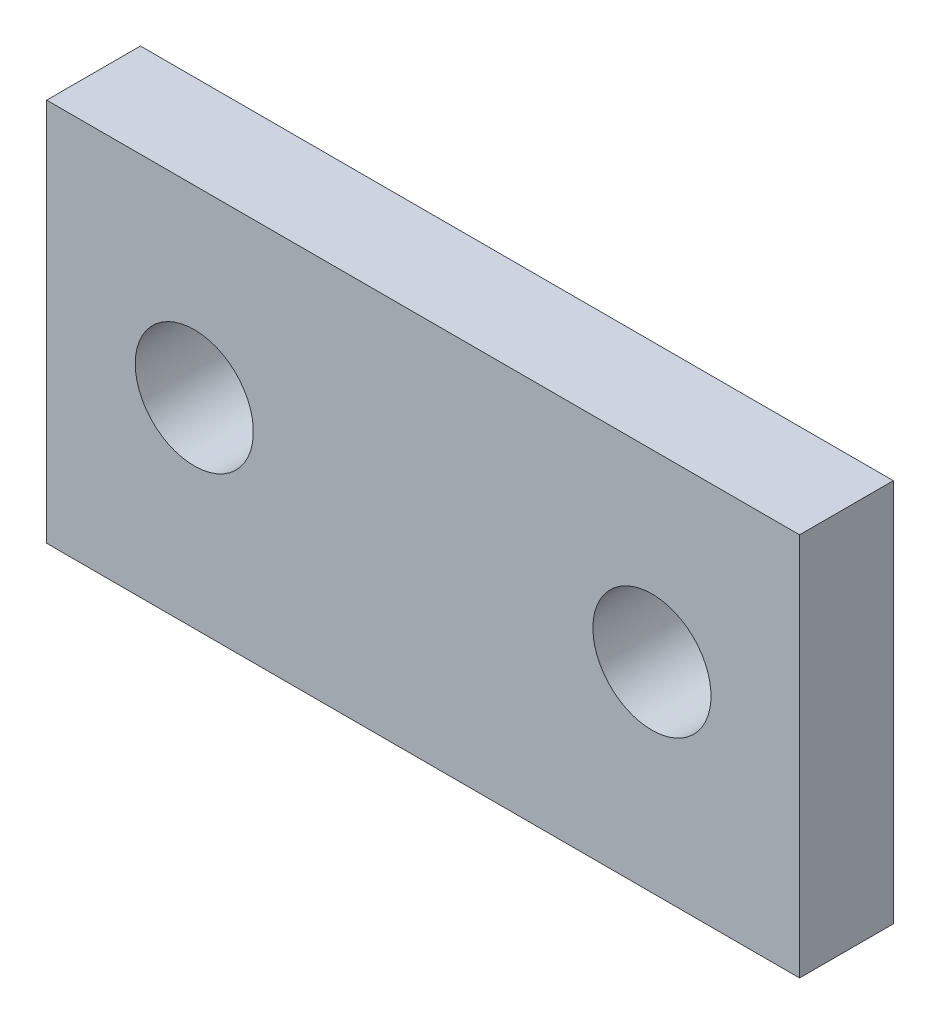
SolidWorks part; units mm, degrees
ref_plane "Front" through (0, 0, 0) normal (0, 0, 1) x (1, 0, 0)
ref_plane "Top" through (0, 0, 0) normal (0, 1, 0) x (1, 0, 0)
ref_plane "Right" through (0, 0, 0) normal (1, 0, 0) x (0, 0, -1)
sketch "Sketch1" plane through (0, 0, 0) normal (0, 0, 1) x (1, 0, 0)
  line L1 (-12.7408, 6.2308) -> (12.7592, 6.2308)
  line L2 (-12.7408, 6.2308) -> (-12.7408, -6.7692)
  line L3 (-12.7408, -6.7692) -> (12.7592, -6.7692)
  line L4 (12.7592, 6.2308) -> (12.7592, -6.7692)
  dimension "D1" = 13
  dimension "D2" = 25.5
extrude "Boss-Extrude1" add sketch "Sketch1" along normal blind 3.175
sketch "Sketch2" plane through (0, 0, 0) normal (0, 0, -1) x (-1, 0, 0)
  line L1 (-12.7592, -6.7692) -> (-12.7592, 6.2308) construction
  circle A0 centre (-7.7592, 0) radius 2
  circle A1 centre (7.7408, 0) radius 2
  dimension "D1" = 4
  dimension "D2" = 15.5
  dimension "D3" = 5
extrude "Cut-Extrude1" cut sketch "Sketch2" against normal through all
